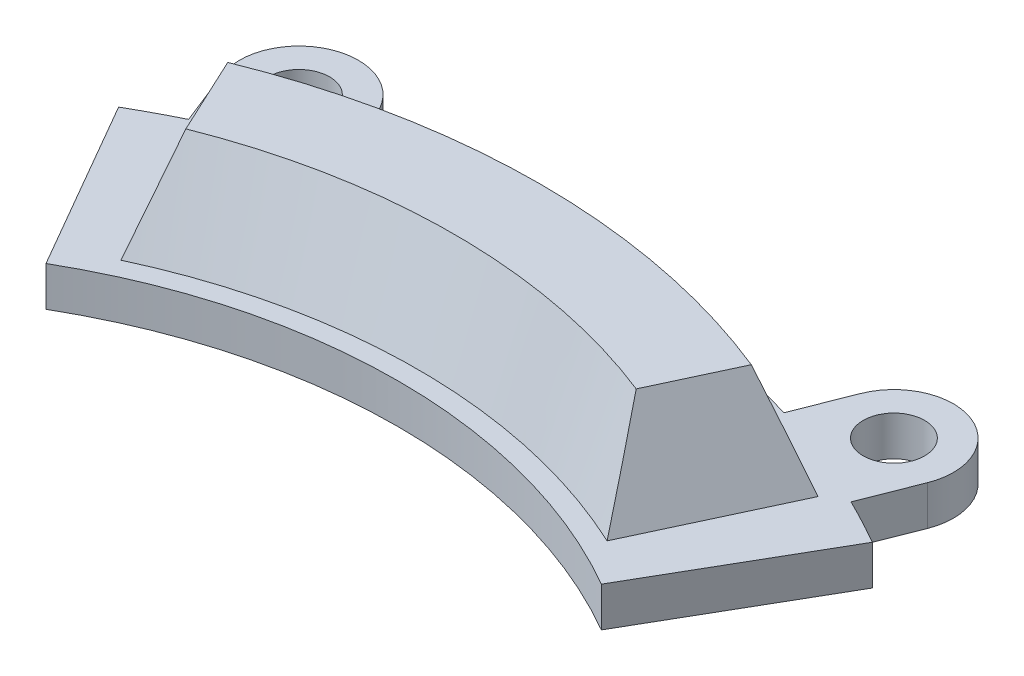
SolidWorks part; units mm, degrees
ref_plane "Front Plane" through (0, 0, 0) normal (0, 0, 1) x (1, 0, 0)
ref_plane "Top Plane" through (0, 0, 0) normal (0, 1, 0) x (1, 0, 0)
ref_plane "Right Plane" through (0, 0, 0) normal (1, 0, 0) x (0, 0, -1)
sketch "Sketch1" plane through (0, 0, 0) normal (0, 1, 0) x (1, 0, 0)
  line L0 (14, 24.2487) -> (19, 32.909)
  line L1 (-14, 24.2487) -> (-19, 32.909)
  line L7 (11.1183, 36.3371) -> (12.2095, 39.1015)
  line L8 (-16.6992, 34.1341) -> (-17.7905, 36.8985)
  line L9 (-11.1183, 36.3371) -> (-12.2095, 39.1015)
  line L11 (16.6992, 34.1341) -> (17.7905, 36.8985)
  arc A0 (14, 24.2487) -> (-14, 24.2487) centre (0, 0) ccw
  arc A1 (19, 32.909) -> (16.6992, 34.1341) centre (0, 0) ccw
  circle A2 centre (0, 0) radius 33 construction
  circle A4 centre (-15, 38) radius 1.55
  circle A5 centre (15, 38) radius 1.55
  arc A7 (-12.2095, 39.1015) -> (-17.7905, 36.8985) centre (-15, 38) ccw
  arc A8 (-16.6992, 34.1341) -> (-19, 32.909) centre (0, 0) ccw
  arc A10 (17.7905, 36.8985) -> (12.2095, 39.1015) centre (15, 38) ccw
  arc A11 (11.1183, 36.3371) -> (-11.1183, 36.3371) centre (0, 0) ccw
  point P6 (7.5, 19)
extrude "Boss-Extrude1" add sketch "Sketch1" along normal blind 2
sketch "Sketch2" plane through (0, 2, 0) normal (0, 1, 0) x (1, 0, 0)
  line L0 (-12.2559, 26.2829) -> (-15.6369, 33.5334)
  line L1 (12.2559, 26.2829) -> (15.6369, 33.5334)
  arc A0 (15.6369, 33.5334) -> (-15.6369, 33.5334) centre (0, 0) ccw
  arc A1 (12.2559, 26.2829) -> (-12.2559, 26.2829) centre (0, 0) ccw
extrude "Boss-Extrude2" add sketch "Sketch2" along normal blind 5 draft 20
